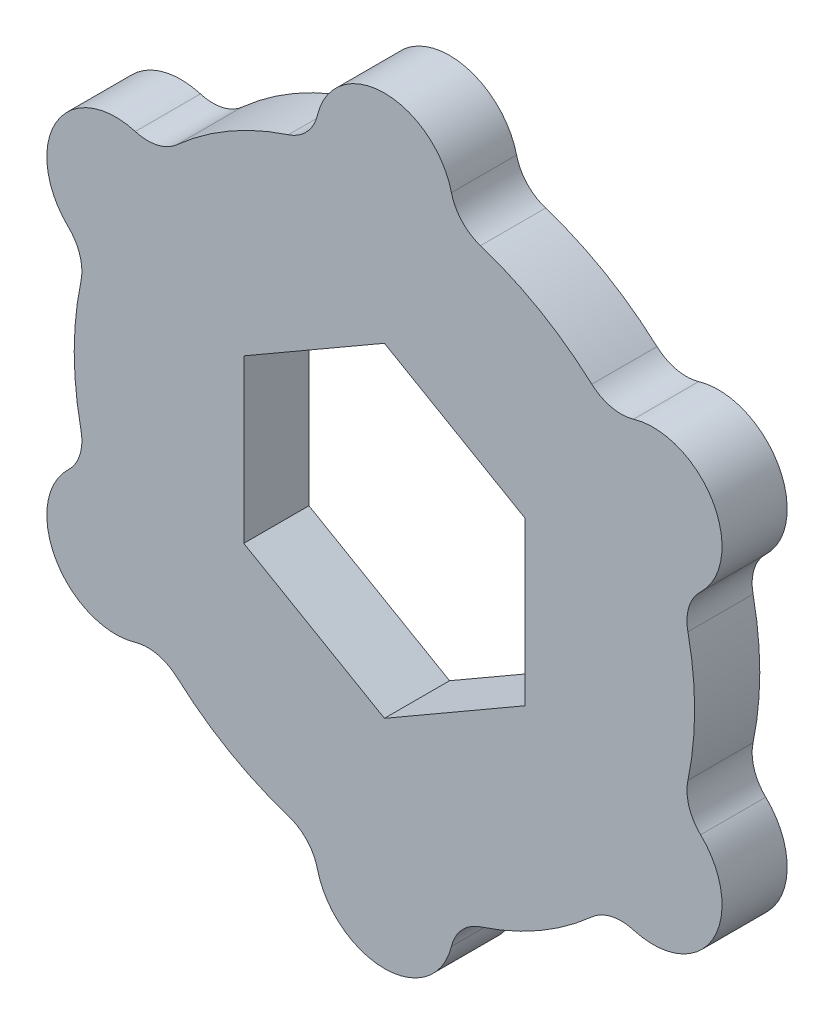
SolidWorks part; units mm, degrees
material "PET"
ref_plane "Front Plane" through (0, 0, 0) normal (0, 0, 1) x (1, 0, 0)
ref_plane "Top Plane" through (0, 0, 0) normal (0, 1, 0) x (1, 0, 0)
ref_plane "Right Plane" through (0, 0, 0) normal (1, 0, 0) x (0, 0, -1)
sketch "Sketch1" plane through (0, 0, 0) normal (0, 0, 1) x (1, 0, 0)
  line L1 (0, 7.479) -> (-6.477, 3.7395)
  line L2 (-6.477, 3.7395) -> (-6.477, -3.7395)
  line L3 (-6.477, -3.7395) -> (0, -7.479)
  line L4 (0, -7.479) -> (6.477, -3.7395)
  line L5 (6.477, -3.7395) -> (6.477, 3.7395)
  line L6 (6.477, 3.7395) -> (0, 7.479)
  arc A0 (-13.6455, 4.2348) -> (-13.6455, -4.2348) centre (0, 0) ccw
  arc A1 (3.1553, 13.9347) -> (-3.1553, 13.9347) centre (0, 14.2875) ccw
  arc A2 (13.6455, 4.2348) -> (10.4902, 9.7) centre (12.3733, 7.1438) ccw
  arc A3 (10.4902, -9.7) -> (13.6455, -4.2348) centre (12.3733, -7.1437) ccw
  arc A4 (-3.1553, -13.9347) -> (3.1553, -13.9347) centre (0, -14.2875) ccw
  arc A5 (-13.6455, -4.2348) -> (-10.4902, -9.7) centre (-12.3733, -7.1438) ccw
  arc A6 (-10.4902, 9.7) -> (-13.6455, 4.2348) centre (-12.3733, 7.1437) ccw
  arc A7 (-13.6455, 4.2348) -> (-10.4902, 9.7) centre (-12.3733, 7.1437) ccw construction
  arc A8 (-10.4902, 9.7) -> (-13.6455, 4.2348) centre (0, 0) ccw construction
  arc A9 (-3.1553, 13.9347) -> (3.1553, 13.9347) centre (0, 14.2875) ccw construction
  arc A10 (3.1553, 13.9347) -> (-3.1553, 13.9347) centre (0, 0) ccw construction
  arc A11 (-3.1553, 13.9347) -> (-10.4902, 9.7) centre (0, 0) ccw
  arc A12 (10.4902, 9.7) -> (13.6455, 4.2348) centre (12.3733, 7.1438) ccw construction
  arc A13 (13.6455, 4.2348) -> (10.4902, 9.7) centre (0, 0) ccw construction
  arc A14 (10.4902, 9.7) -> (3.1553, 13.9347) centre (0, 0) ccw
  arc A15 (13.6455, -4.2348) -> (10.4902, -9.7) centre (12.3733, -7.1437) ccw construction
  arc A16 (10.4902, -9.7) -> (13.6455, -4.2348) centre (0, 0) ccw construction
  arc A17 (13.6455, -4.2348) -> (13.6455, 4.2348) centre (0, 0) ccw
  arc A18 (3.1553, -13.9347) -> (-3.1553, -13.9347) centre (0, -14.2875) ccw construction
  arc A19 (-3.1553, -13.9347) -> (3.1553, -13.9347) centre (0, 0) ccw construction
  arc A20 (3.1553, -13.9347) -> (10.4902, -9.7) centre (0, 0) ccw
  arc A21 (-10.4902, -9.7) -> (-13.6455, -4.2348) centre (-12.3733, -7.1438) ccw construction
  arc A22 (-13.6455, -4.2348) -> (-10.4902, -9.7) centre (0, 0) ccw construction
  arc A23 (-10.4902, -9.7) -> (-3.1553, -13.9347) centre (0, 0) ccw
  circle A24 centre (0, 0) radius 6.477 construction
  point P18 (0, 0)
  dimension "D1" = 28.575
  dimension "D2" = 6.35
  dimension "D4" = 12.954
  dimension "D3" = 6
extrude "Boss-Extrude1" add sketch "Sketch1" along normal mid plane 3
fillet "Fillet1" radius 2.0193 12 edges at (10.4902, 9.7, 0) (13.6455, 4.2348, 0) (13.6455, -4.2348, 0) (10.4902, -9.7, 0) (3.1553, -13.9347, 0) (-3.1553, -13.9347, 0) (-10.4902, -9.7, 0) (-13.6455, -4.2348, 0) (-13.6455, 4.2348, 0) (-3.1553, 13.9347, 0) (3.1553, 13.9347, 0) (-10.4902, 9.7, 0)
